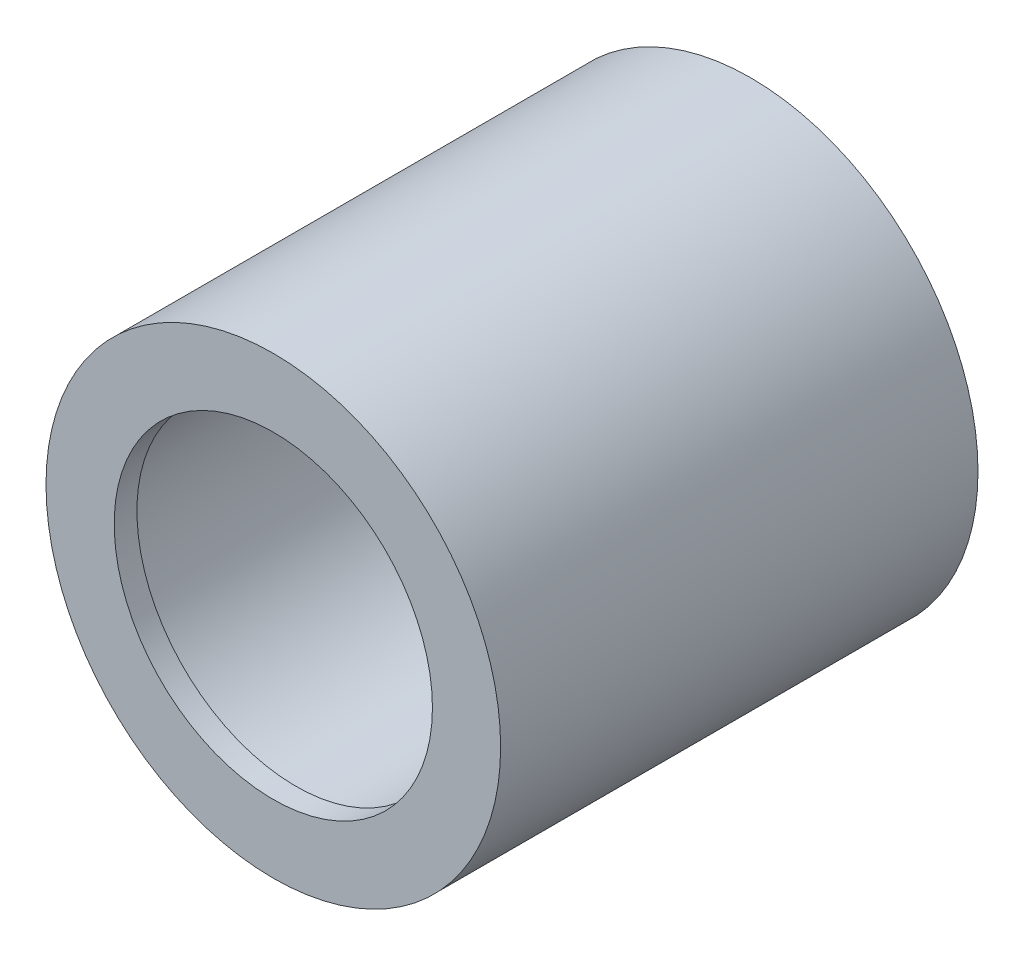
SolidWorks part; units mm, degrees
ref_plane "Front Plane" through (0, 0, 0) normal (0, 0, 1) x (1, 0, 0)
ref_plane "Top Plane" through (0, 0, 0) normal (0, 1, 0) x (1, 0, 0)
ref_plane "Right Plane" through (0, 0, 0) normal (1, 0, 0) x (0, 0, -1)
sketch "Sketch1" plane through (0, 0, 0) normal (0, 0, 1) x (1, 0, 0)
  circle A0 centre (0, 0) radius 5
  dimension "D1" = 10
extrude "Boss-Extrude1" add sketch "Sketch1" along normal blind 10
sketch "Sketch2" plane through (0, 0, 10) normal (0, 0, 1) x (1, 0, 0)
  circle A0 centre (0, 0) radius 3.65
  dimension "D1" = 7.3
extrude "Cut-Extrude1" cut sketch "Sketch2" against normal up to surface (10 mm away) up to face at (5, 0, 0)
sketch "Sketch3" plane through (0, 0, 10) normal (0, 0, 1) x (1, 0, 0)
  circle A0 centre (0, 0) radius 3.65 construction
  circle A1 centre (0, 0) radius 3.65
  circle A2 centre (0, 0) radius 3.5 construction
  circle A3 centre (0, 0) radius 3.5
extrude "Boss-Extrude2" [suppressed] add sketch "Sketch3" against normal blind 0.1
chamfer "Chamfer1" [suppressed] distance 1 angle 45
sketch "Sketch4" plane through (0, 0, 0) normal (0, 0, -1) x (-1, 0, 0)
  line L1 (0, 4.2147) -> (-3.65, 2.1073)
  line L2 (-3.65, 2.1073) -> (-3.65, -2.1073)
  line L3 (-3.65, -2.1073) -> (0, -4.2147)
  line L4 (0, -4.2147) -> (3.65, -2.1073)
  line L5 (3.65, -2.1073) -> (3.65, 2.1073)
  line L6 (3.65, 2.1073) -> (0, 4.2147)
  circle A1 centre (0, 0) radius 3.65 construction
  circle A2 centre (0, 0) radius 3.65 construction
  point P1 (0, 0)
extrude "Cut-Extrude2" cut sketch "Sketch4" against normal blind 5
sketch "Sketch5" plane through (0, 0, 10) normal (0, 0, 1) x (1, 0, 0)
  circle A0 centre (0, 0) radius 3.5
  circle A1 centre (0, 0) radius 5 construction
  circle A2 centre (0, 0) radius 5
  dimension "D1" = 7
extrude "Boss-Extrude3" add sketch "Sketch5" along normal blind 0.5
